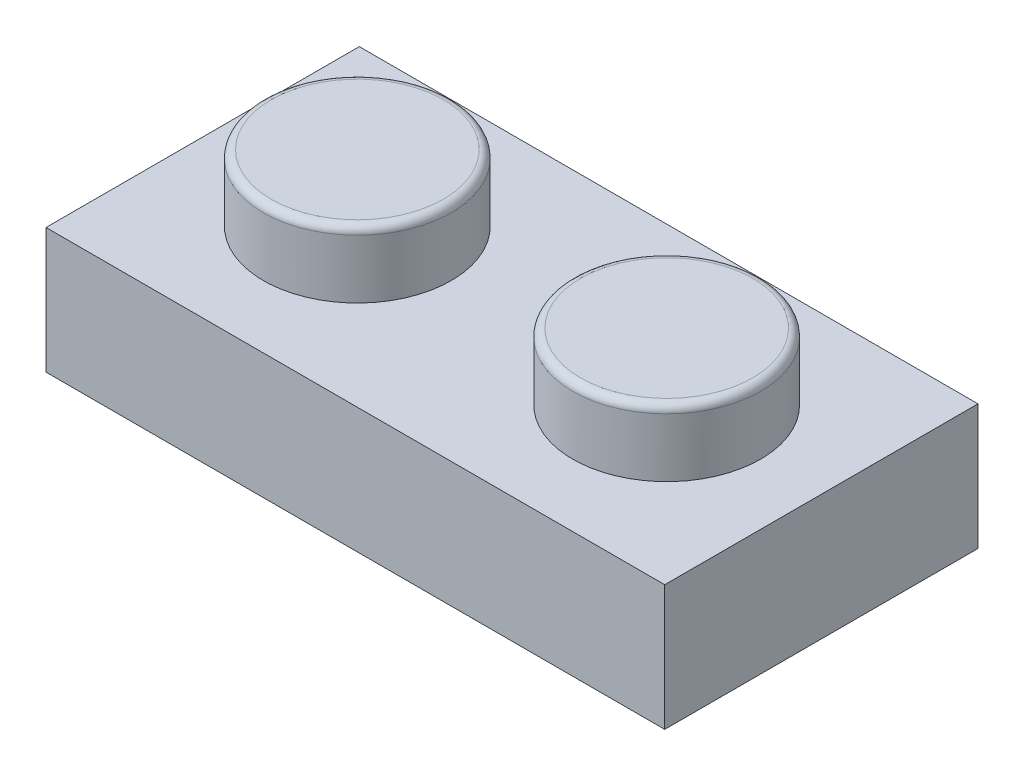
SolidWorks part; units mm, degrees
ref_plane "Plan de face" through (0, 0, 0) normal (0, 0, 1) x (1, 0, 0)
ref_plane "Plan de dessus" through (0, 0, 0) normal (0, 1, 0) x (1, 0, 0)
ref_plane "Plan de droite" through (0, 0, 0) normal (1, 0, 0) x (0, 0, -1)
sketch "Esquisse1" plane through (0, 0, 0) normal (0, 1, 0) x (1, 0, 0)
  line L0 (0, 0) -> (0, 8)
  line L1 (0, 8) -> (15.8, 8)
  line L2 (15.8, 8) -> (15.8, 0)
  line L3 (15.8, 0) -> (0, 0)
  dimension "D1" = 8
  dimension "D2" = 15.8
extrude "Boss.-Extru.1" add sketch "Esquisse1" along normal blind 3.2
sketch "Esquisse2" plane through (0, 3.2, 0) normal (0, 1, 0) x (1, 0, 0)
  line L0 (0, 4) -> (15.8, 4) construction
  line L1 (0, 8) -> (0, 0) construction
  line L2 (15.8, 0) -> (15.8, 8) construction
  circle A0 centre (3.95, 4) radius 2.4
  circle A1 centre (11.85, 4) radius 2.4
  dimension "D1" = 4.8
  dimension "D2" = 3.95
  dimension "D3" = 2
extrude "Boss.-Extru.2" add sketch "Esquisse2" along normal blind 1.7
sketch "Esquisse3" plane through (0, 0, 0) normal (0, -1, 0) x (1, 0, 0)
  line L0 (0, -4) -> (15.8, -4) construction
  line L1 (0, -8) -> (0, 0) construction
  line L2 (15.8, 0) -> (15.8, -8) construction
  circle A0 centre (3.95, -4) radius 1.9
  circle A1 centre (11.85, -4) radius 1.9
  dimension "D1" = 3.8
  dimension "D2" = 3.95
  dimension "D3" = 2
extrude "Enlèv. mat.-Extru.1" cut sketch "Esquisse3" against normal blind 1.7
fillet "Congé1" radius 0.2 4 edges at (3.95, 4.9, -1.6) (11.85, 4.9, -1.6) (11.85, 1.7, -5.9) (3.95, 1.7, -5.9)
